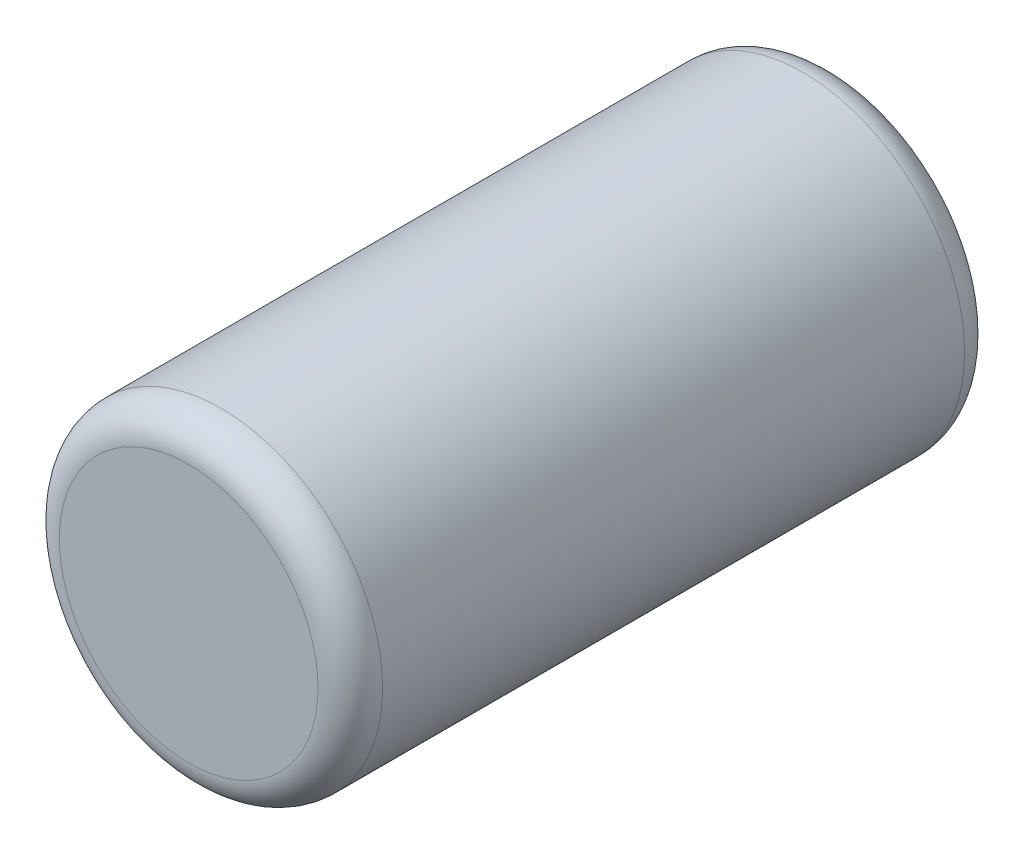
SolidWorks part; units mm, degrees
ref_plane "Front Plane" through (0, 0, 0) normal (0, 0, 1) x (1, 0, 0)
ref_plane "Top Plane" through (0, 0, 0) normal (0, 1, 0) x (1, 0, 0)
ref_plane "Right Plane" through (0, 0, 0) normal (1, 0, 0) x (0, 0, -1)
sketch "Sketch1" plane through (0, 0, 0) normal (0, 0, 1) x (1, 0, 0)
  circle A0 centre (0, 0) radius 2.5
  dimension "D1" = 5
extrude "Boss-Extrude1" add sketch "Sketch1" along normal blind 10
fillet "Fillet1" radius 0.5 2 edges at (2.5, 0, 0) (2.5, 0, 10)
